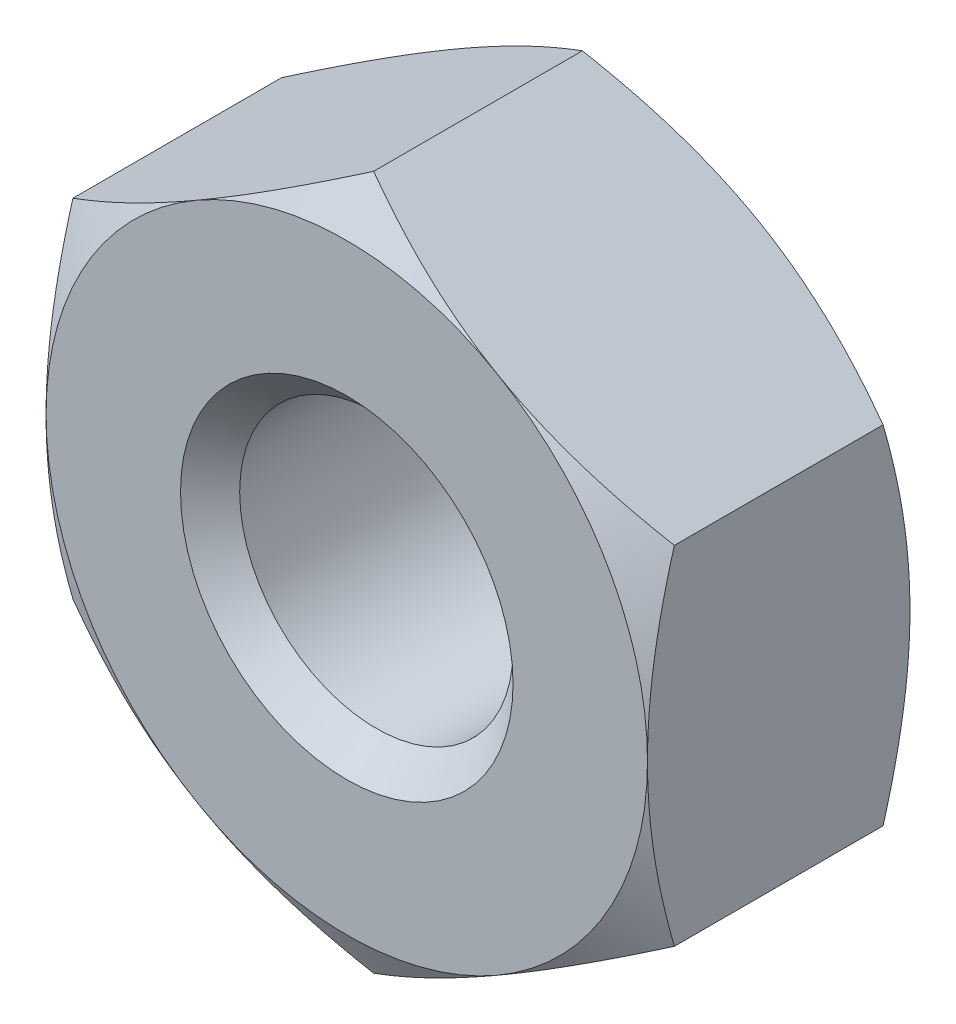
SolidWorks part; units mm, degrees
material "Plain Carbon Steel"
ref_plane "Front Plane" through (0, 0, 0) normal (0, 0, 1) x (1, 0, 0)
ref_plane "Top Plane" through (0, 0, 0) normal (0, 1, 0) x (1, 0, 0)
ref_plane "Right Plane" through (0, 0, 0) normal (1, 0, 0) x (0, 0, -1)
sketch "Sketch2" plane through (0, 0, 0) normal (0, 0, 1) x (1, 0, 0)
  line L0 (2.75, 1.5877) -> (2.75, -1.5877)
  line L1 (-2.75, 1.5877) -> (-2.75, -1.5877)
  line L2 (2.75, 1.5877) -> (0, 3.1754)
  line L3 (0, 3.1754) -> (-2.75, 1.5877)
  line L4 (-2.75, -1.5877) -> (0, -3.1754)
  line L5 (0, -3.1754) -> (2.75, -1.5877)
  circle A0 centre (0, 0) radius 1.25
  dimension "D3" = 2.5
  dimension "D1" = 5.5
  dimension "D2" = 120
  dimension "D4" = 2.75
extrude "Boss-Extrude1" add sketch "Sketch2" along normal mid plane 2.4
sketch "Sketch3" plane through (0, 0, -1.2) normal (0, 0, -1) x (-1, 0, 0)
  line L0 (0, 3.1754) -> (2.75, 1.5877) construction
  line L1 (-2.75, 1.5877) -> (0, 3.1754) construction
  line L2 (-2.75, 1.5877) -> (-2.75, -1.5877) construction
  line L3 (0, -3.1754) -> (-2.75, -1.5877) construction
  line L4 (2.75, -1.5877) -> (0, -3.1754) construction
  line L5 (2.75, 1.5877) -> (2.75, -1.5877) construction
  line L6 (0, 3.1754) -> (2.75, 1.5877) construction
  line L7 (-2.75, 1.5877) -> (0, 3.1754) construction
  line L8 (-2.75, 1.5877) -> (-2.75, -1.5877) construction
  line L9 (0, -3.1754) -> (-2.75, -1.5877) construction
  line L10 (2.75, -1.5877) -> (0, -3.1754) construction
  line L11 (2.75, 1.5877) -> (2.75, -1.5877) construction
  circle A0 centre (0, 0) radius 2.75 construction
sketch "Sketch4" plane through (0, 0, 0) normal (1, 0, 0) x (0, 0, -1)
  line L0 (1.2, -2.75) -> (1.2, 2.75) construction
  line L1 (1.2, -2.75) -> (1.2, 2.75) construction
  line L2 (1.2, 2.75) -> (1.2, 4.3287)
  line L3 (1.2, 4.3287) -> (0.2886, 4.3287)
  line L4 (0.2886, 4.3287) -> (1.2, 2.75)
  line L6 (-2.9945, 0) -> (4.4636, 0) construction
  dimension "D1" = 30
revolve "Cut-Revolve2" cut sketch "Sketch4" angle 360 about L6
mirror "Mirror1" about plane through (0, 0, 0) normal (0, 0, 1) of "Cut-Revolve2"
chamfer "Chamfer1" distance 0.2705 angle 45 2 edges at (1.25, 0, -1.2) (1.25, 0, 1.2)
ref_plane "Plane1" through (0, 0, -1.7) normal (0, 0, -1) x (-1, 0, 0)
